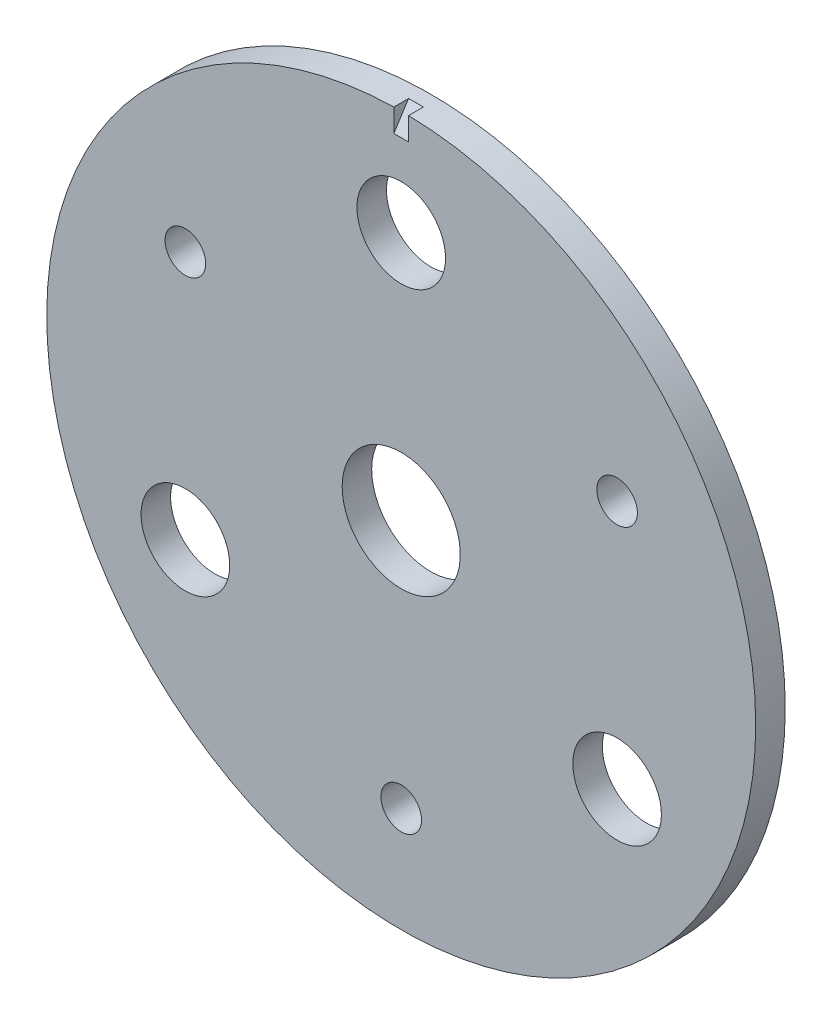
SolidWorks part; units mm, degrees
material "1.7225 (42CrMo4)"
ref_plane "Front Plane" through (0, 0, 0) normal (0, 0, 1) x (1, 0, 0)
ref_plane "Top Plane" through (0, 0, 0) normal (0, 1, 0) x (1, 0, 0)
ref_plane "Right Plane" through (0, 0, 0) normal (1, 0, 0) x (0, 0, -1)
sketch "Sketch1" plane through (0, 0, 0) normal (0, 0, 1) x (1, 0, 0)
  circle A0 centre (0, 0) radius 48
  circle A1 centre (0, 0) radius 8
  dimension "D1" = 96
  dimension "D2" = 16
extrude "EX_Carrier_Front_Plate_4mm" add sketch "Sketch1" along normal mid plane 4
sketch "Sketch2" plane through (0, 0, 2) normal (0, 0, 1) x (1, 0, 0)
  line L0 (0, 0) -> (0, 33.75) construction
  circle A0 centre (0, 33.75) radius 6
  dimension "D2" = 12
  dimension "D1" = 33.75
extrude "CUT_Pin_Hole_Ø12" cut sketch "Sketch2" against normal through all both and the other way through all contours A0
pattern_circular "PAT_Pin_Holes_3x120" count 3 over 360 about axis through (0, 0, 0) along (0, 0, 1) of "CUT_Pin_Hole_Ø12"
sketch "Sketch3" plane through (0, 0, 0) normal (1, 0, 0) x (0, 0, -1)
  line L0 (-2, 44.8897) -> (0, 48)
  line L1 (-2, 48) -> (-2, -48) construction
  line L2 (2, 48) -> (-2, 48) construction
  line L3 (0, 48) -> (-2, 48)
  line L4 (-2, 48) -> (-2, 44.8897)
extrude "Cut-Extrude1" cut sketch "Sketch3" against normal mid plane 2
sketch "Sketch4" plane through (0, 0, 0) normal (0, 0, 1) x (1, 0, 0)
  circle A0 centre (0, -33.75) radius 2.75
extrude "Cut-Extrude2" cut sketch "Sketch4" along normal through all
sketch "Sketch5" plane through (0, 0, 0) normal (0, 0, 1) x (1, 0, 0)
  circle A0 centre (0, -33.75) radius 2.75
extrude "Cut-Extrude3" cut sketch "Sketch5" against normal through all
ref_axis "Axis1" through (0, 0, -2.2083) along (0, 0, 1)
pattern_circular "CirPattern1" count 3 over 360 about axis through (0, 0, 0) along (0, 0, 1) of "Cut-Extrude2"
pattern_circular "CirPattern2" count 3 over 360 about axis through (0, 0, -2.2083) along (0, 0, 1) of "Cut-Extrude3"
